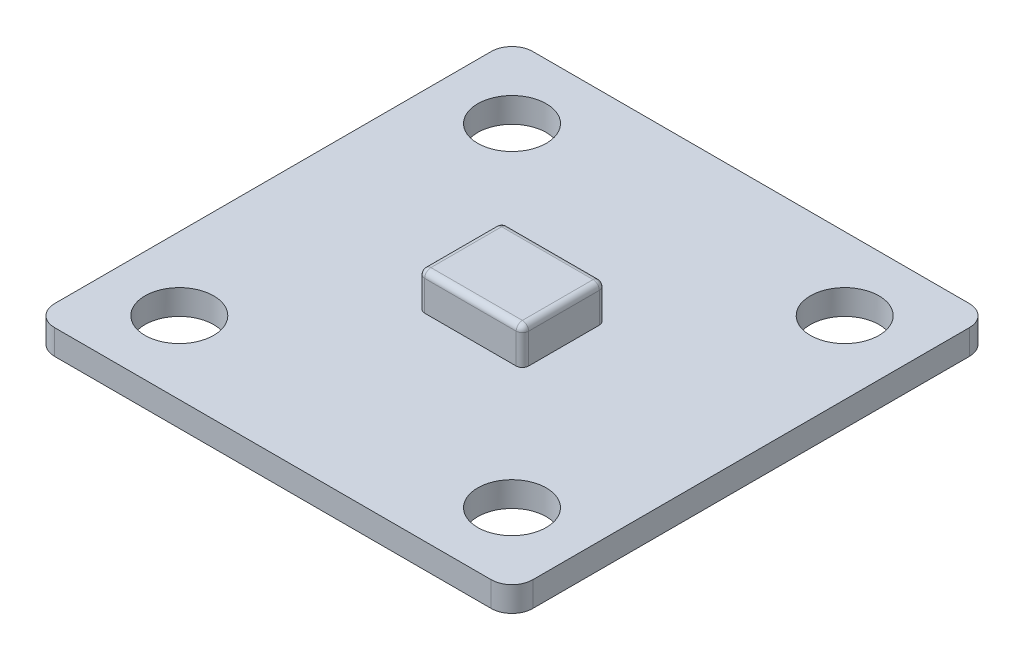
SolidWorks part; units mm, degrees
ref_plane "Front Plane" through (0, 0, 0) normal (0, 0, 1) x (1, 0, 0)
ref_plane "Top Plane" through (0, 0, 0) normal (0, 1, 0) x (1, 0, 0)
ref_plane "Right Plane" through (0, 0, 0) normal (1, 0, 0) x (0, 0, -1)
sketch "Sketch1" plane through (0, 0, 0) normal (0, 1, 0) x (1, 0, 0)
  line L1 (-11.5, -11.5) -> (11.5, -11.5)
  line L2 (-11.5, -11.5) -> (-11.5, 11.5)
  line L3 (-11.5, 11.5) -> (11.5, 11.5)
  line L4 (11.5, -11.5) -> (11.5, 11.5)
  line L5 (-11.5, -11.5) -> (11.5, 11.5) construction
  line L6 (-11.5, 11.5) -> (11.5, -11.5) construction
  point P0 (0, 0)
  dimension "D1" = 23
extrude "Boss-Extrude1" add sketch "Sketch1" along normal blind 1.2
fillet "Fillet1" radius 1 4 edges at (11.5, 0.6, -11.5) (-11.5, 0.6, -11.5) (11.5, 0.6, 11.5) (-11.5, 0.6, 11.5)
sketch "Sketch2" plane through (0, 1.2, 0) normal (0, 1, 0) x (1, 0, 0)
  line L1 (-2.5, -2) -> (2.5, -2)
  line L2 (-2.5, -2) -> (-2.5, 2)
  line L3 (-2.5, 2) -> (2.5, 2)
  line L4 (2.5, -2) -> (2.5, 2)
  line L5 (-2.5, -2) -> (2.5, 2) construction
  line L6 (-2.5, 2) -> (2.5, -2) construction
  point P0 (0, 0)
  dimension "D1" = 5
  dimension "D2" = 4
extrude "Boss-Extrude2" add sketch "Sketch2" along normal blind 1.75
fillet "Fillet2" radius 0.3 8 edges at (0, 2.95, 2) (-2.5, 2.95, 0) (0, 2.95, -2) (2.5, 2.95, 0) (-2.5, 2.075, -2) (-2.5, 2.075, 2) (2.5, 2.075, -2) (2.5, 2.075, 2)
sketch "Sketch4" plane through (0, 1.2, 0) normal (0, 1, 0) x (1, 0, 0)
  line L1 (-8, -8) -> (8, -8) construction
  line L2 (-8, -8) -> (-8, 8) construction
  line L3 (-8, 8) -> (8, 8) construction
  line L4 (8, -8) -> (8, 8) construction
  line L5 (-8, -8) -> (8, 8) construction
  line L6 (-8, 8) -> (8, -8) construction
  circle A0 centre (-8, 8) radius 1.65
  circle A1 centre (8, 8) radius 1.65
  circle A2 centre (8, -8) radius 1.65
  circle A3 centre (-8, -8) radius 1.65
  point P0 (0, 0)
  dimension "D2" = 3.3
  dimension "D1" = 16
extrude "Cut-Extrude1" cut sketch "Sketch4" against normal blind 1.75
